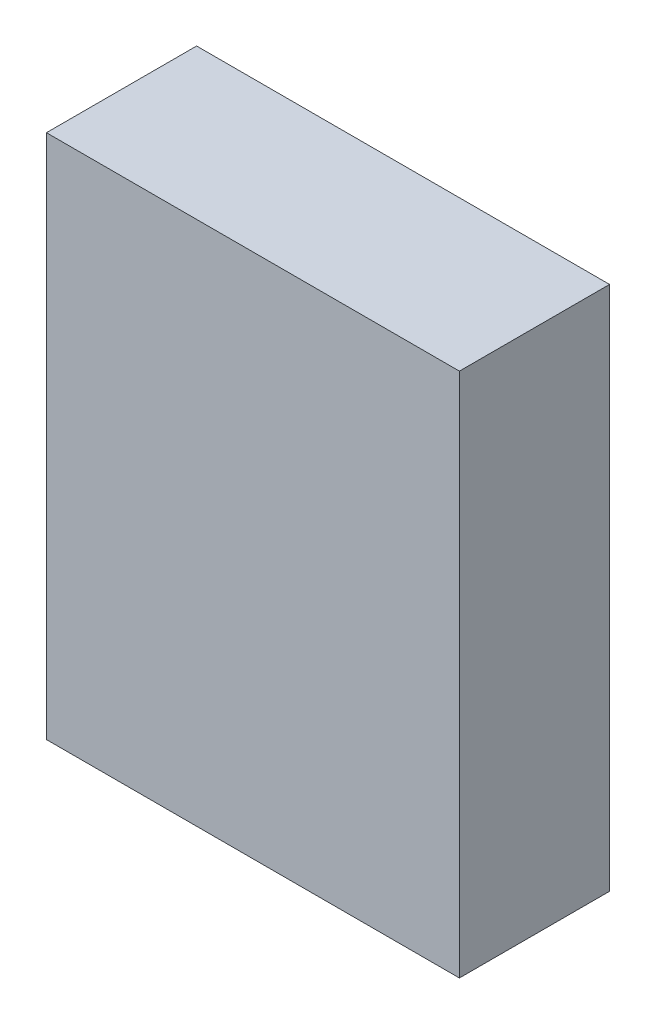
SolidWorks part; units mm, degrees
ref_plane "Front Plane" through (0, 0, 0) normal (0, 0, 1) x (1, 0, 0)
ref_plane "Top Plane" through (0, 0, 0) normal (0, 1, 0) x (1, 0, 0)
ref_plane "Right Plane" through (0, 0, 0) normal (1, 0, 0) x (0, 0, -1)
sketch "Sketch1" plane through (0, 0, 0) normal (0, 0, 1) x (1, 0, 0)
  line L1 (27.5, 35) -> (-27.5, 35)
  line L2 (27.5, 35) -> (27.5, -35)
  line L3 (27.5, -35) -> (-27.5, -35)
  line L4 (-27.5, 35) -> (-27.5, -35)
  line L5 (0, -35) -> (0, 35) construction
  line L6 (27.5, 0) -> (-27.5, 0) construction
  point P0 (0, 0)
  dimension "D1" = 55
  dimension "D2" = 70
extrude "Boss-Extrude1" add sketch "Sketch1" along normal blind 20
